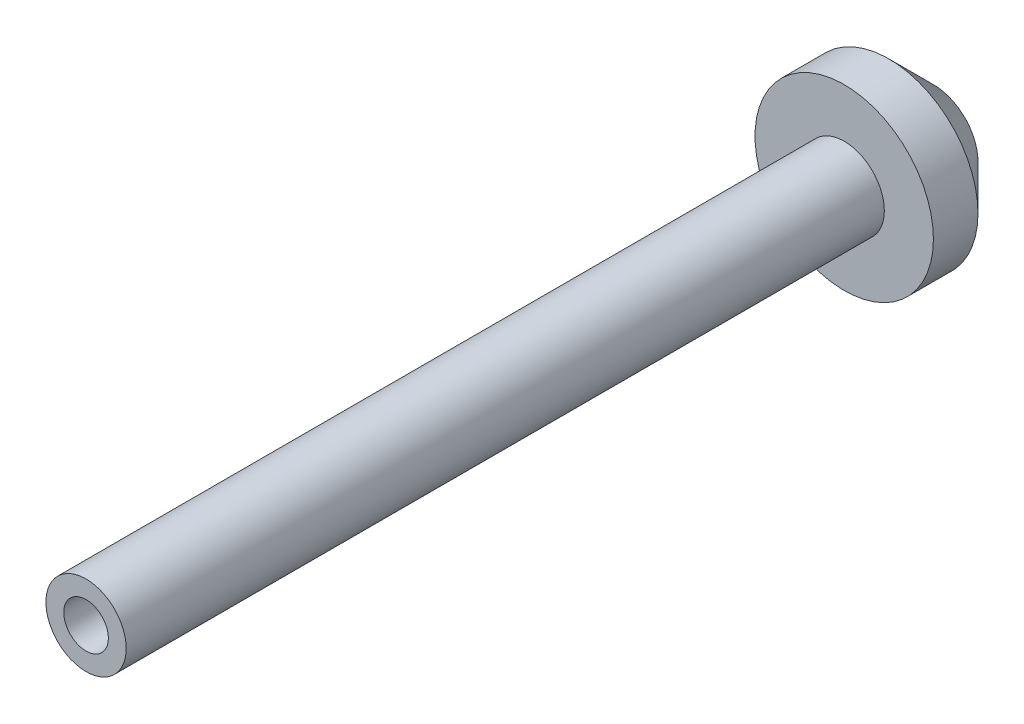
SolidWorks part; units mm, degrees
ref_plane "Front Plane" through (0, 0, 0) normal (0, 0, 1) x (1, 0, 0)
ref_plane "Top Plane" through (0, 0, 0) normal (0, 1, 0) x (1, 0, 0)
ref_plane "Right Plane" through (0, 0, 0) normal (1, 0, 0) x (0, 0, -1)
sketch "Sketch1" plane through (0, 0, 0) normal (0, 0, 1) x (1, 0, 0)
  circle A0 centre (0, 0) radius 5
  dimension "D1" = 10
extrude "Boss-Extrude1" add sketch "Sketch1" along normal blind 5
sketch "Sketch2" plane through (0, 0, 5) normal (0, 0, 1) x (1, 0, 0)
  circle A0 centre (0, 0) radius 2.25
  dimension "D1" = 4.5
extrude "Boss-Extrude2" add sketch "Sketch2" along normal blind 42.5
sketch "Sketch3" plane through (0, 0, 47.5) normal (0, 0, 1) x (1, 0, 0)
  circle A0 centre (0, 0) radius 1.25
  dimension "D1" = 2.5
extrude "Cut-Extrude1" cut sketch "Sketch3" against normal blind 10
chamfer "Chamfer1" distance 2.5 angle 45 1 edges at (5, 0, 0)
